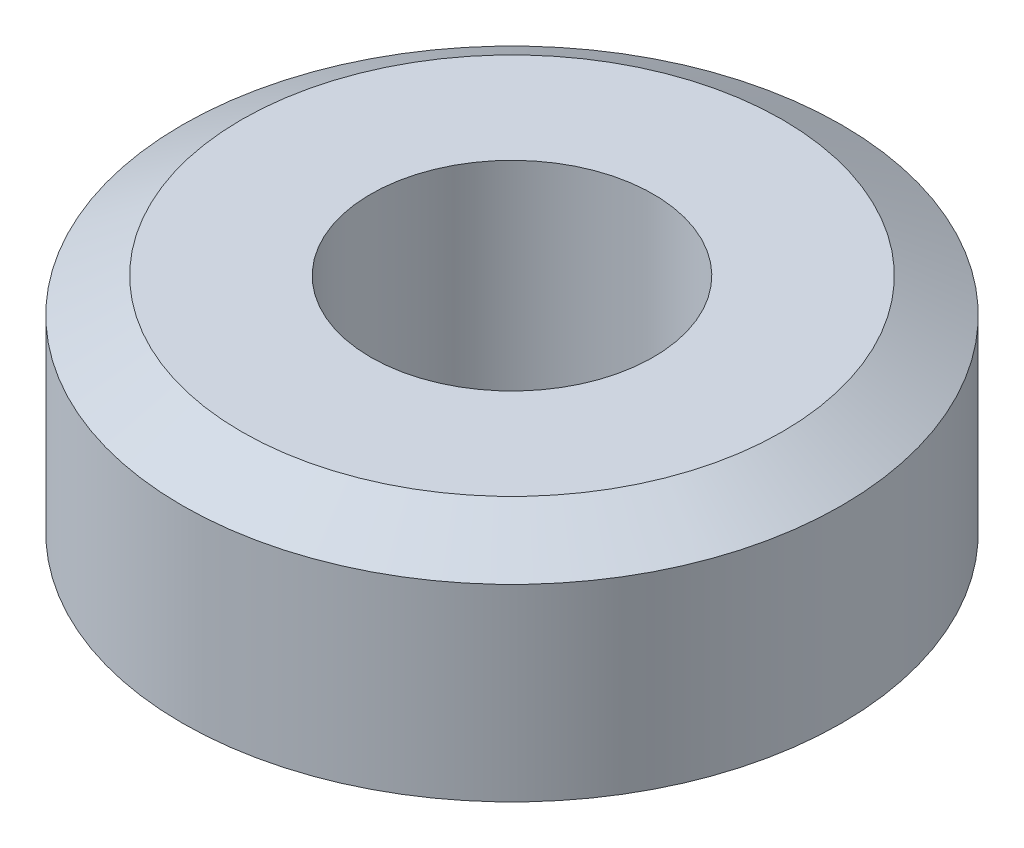
SolidWorks part; units mm, degrees
ref_plane "Спереди" through (0, 0, 0) normal (0, 0, 1) x (1, 0, 0)
ref_plane "Сверху" through (0, 0, 0) normal (0, 1, 0) x (1, 0, 0)
ref_plane "Справа" through (0, 0, 0) normal (1, 0, 0) x (0, 0, -1)
other "Configuration Table"
sketch "Эскиз1" plane through (0, 0, 0) normal (0, 1, 0) x (1, 0, 0)
  circle A0 centre (0, 0) radius 3.85
  circle A1 centre (0, 0) radius 1.65
  dimension "D1" = 3.3
  dimension "D2" = 7.7
extrude "Бобышка-Вытянуть1" add sketch "Эскиз1" along normal blind 3
chamfer "Фаска8" distance 0.4 angle 60 1 edges at (0, 3, 3.85)
chamfer "Фаска10" distance 0.4 angle 60 1 edges at (0, 0, 3.85)
